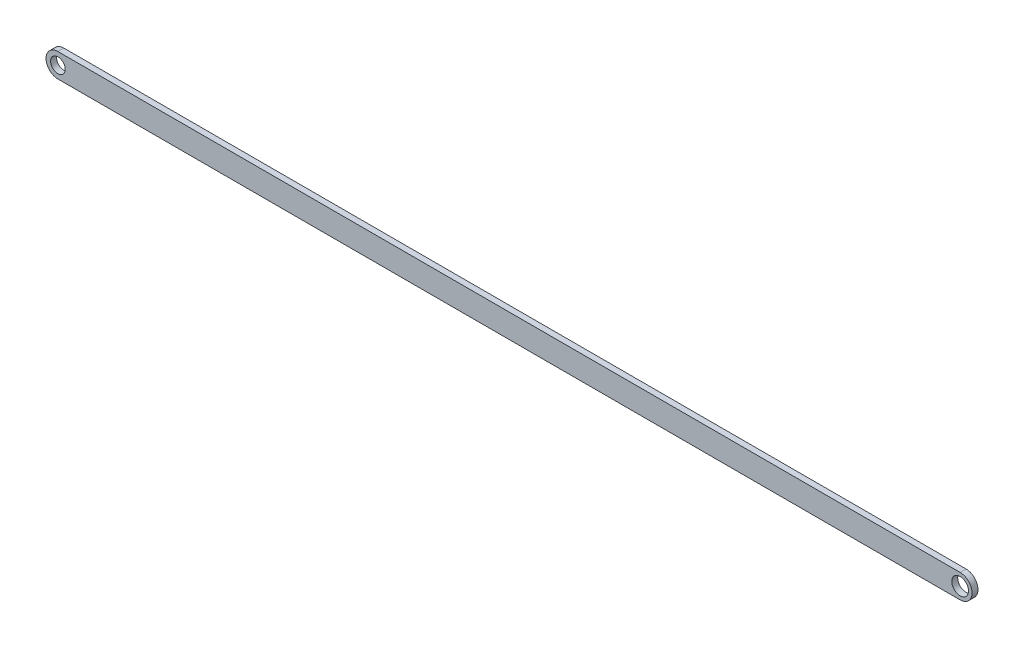
SolidWorks part; units mm, degrees
material "0.6025 (EN-GJL-250)"
ref_plane "前视基准面" through (0, 0, 0) normal (0, 0, 1) x (1, 0, 0)
ref_plane "上视基准面" through (0, 0, 0) normal (0, 1, 0) x (1, 0, 0)
ref_plane "右视基准面" through (0, 0, 0) normal (1, 0, 0) x (0, 0, -1)
sketch "草图1" plane through (0, 0, 0) normal (0, 0, 1) x (1, 0, 0)
  line L0 (-378.7, 0) -> (378.7, 0) construction
  line L1 (-378.7, 10) -> (378.7, 10)
  line L2 (-378.7, -10) -> (378.7, -10)
  arc A0 (-378.7, 10) -> (-378.7, -10) centre (-378.7, 0) ccw
  arc A1 (378.7, -10) -> (378.7, 10) centre (378.7, 0) ccw
  circle A3 centre (378.7, 0) radius 7.0323
  circle A4 centre (-378.7, 0) radius 6.1443
  point P3 (0, 0)
  dimension "D1" = 757.4
  dimension "D2" = 20
extrude "凸台-拉伸1" add sketch "草图1" along normal blind 5
